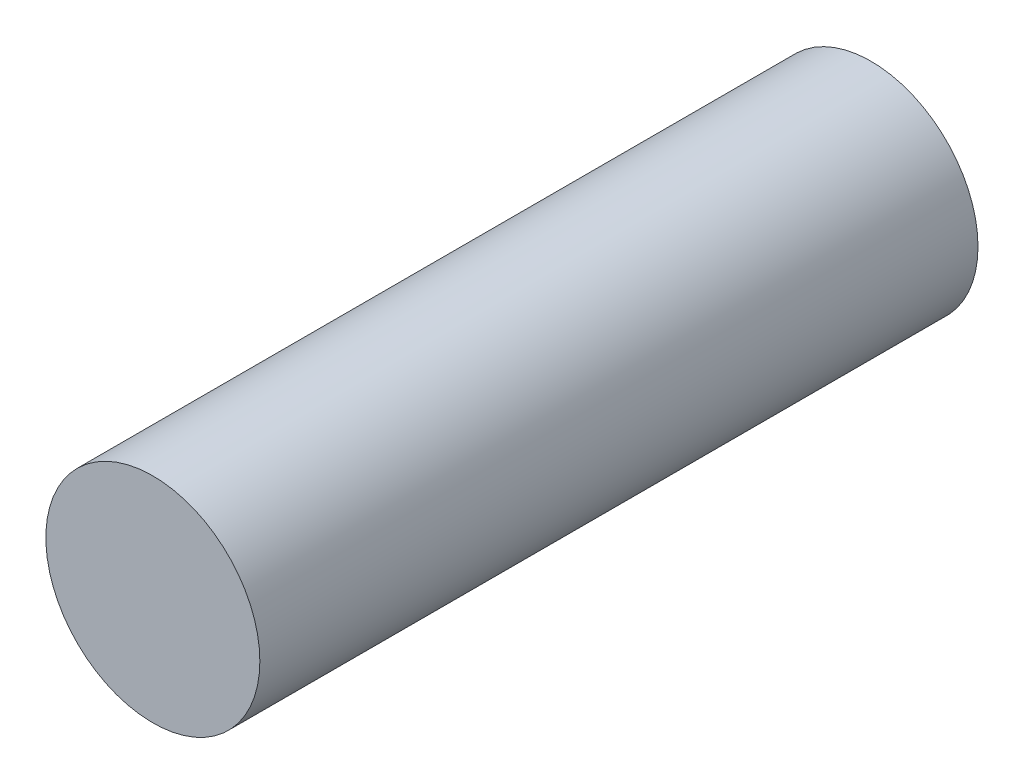
SolidWorks part; units mm, degrees
ref_plane "Front Plane" through (0, 0, 0) normal (0, 0, 1) x (1, 0, 0)
ref_plane "Top Plane" through (0, 0, 0) normal (0, 1, 0) x (1, 0, 0)
ref_plane "Right Plane" through (0, 0, 0) normal (1, 0, 0) x (0, 0, -1)
sketch "Sketch2" plane through (0, 0, 0) normal (0, 0, 1) x (1, 0, 0)
  circle A0 centre (-50.1105, 18.0059) radius 7.45
  dimension "D1" = 14.9
extrude "Boss-Extrude1" add sketch "Sketch2" along normal blind 50
